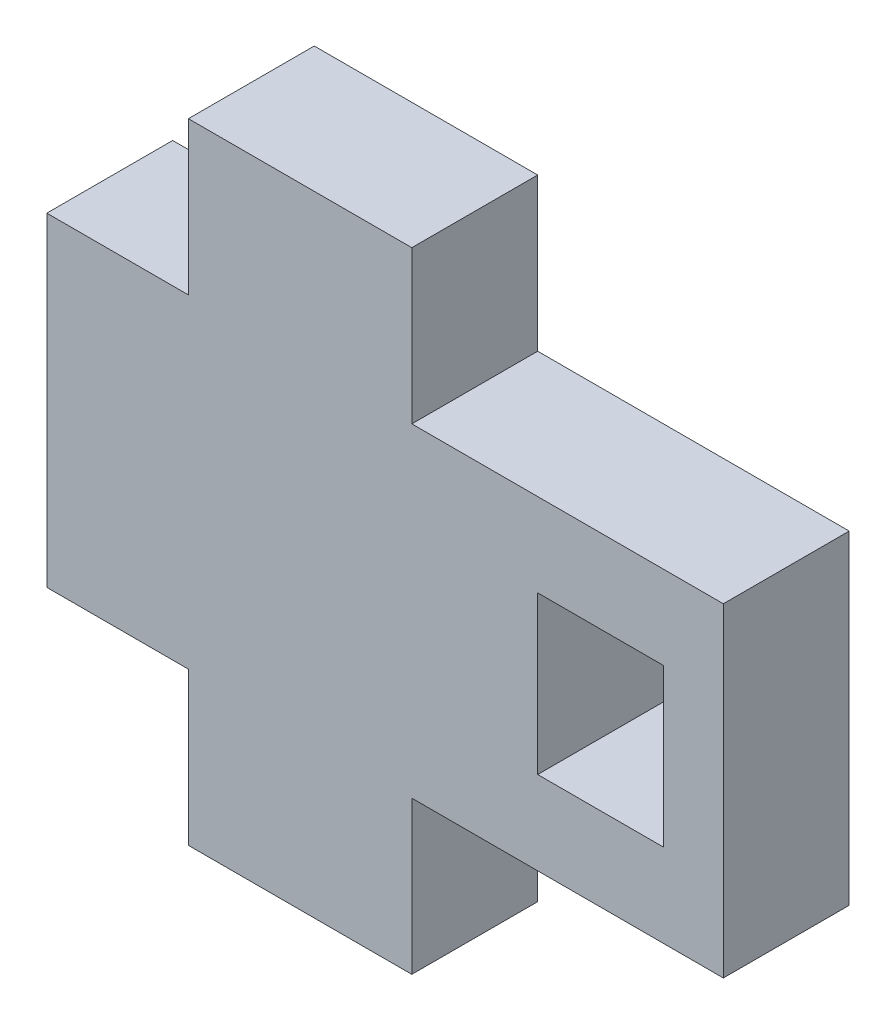
SolidWorks part; units mm, degrees
ref_plane "前视基准面" through (0, 0, 0) normal (0, 0, 1) x (1, 0, 0)
ref_plane "上视基准面" through (0, 0, 0) normal (0, 1, 0) x (1, 0, 0)
ref_plane "右视基准面" through (0, 0, 0) normal (1, 0, 0) x (0, 0, -1)
sketch "草图1" plane through (0, 0, 0) normal (0, 0, 1) x (1, 0, 0)
  line L0 (0, 15.15) -> (0, 20)
  line L1 (0, 0) -> (7.1, 0)
  line L2 (0, 0) -> (0, 4.85)
  line L3 (0, 20) -> (7.1, 20)
  line L4 (7.1, 0) -> (7.1, 4.85)
  line L5 (7.1, 15.15) -> (12.1, 15.15)
  line L7 (7.1, 4.85) -> (12.1, 4.85)
  line L9 (0, 15.15) -> (-4.5, 15.15)
  line L11 (0, 4.85) -> (-4.5, 4.85)
  line L12 (-4.5, 15.15) -> (-4.5, 4.85)
  line L13 (7.1, 15.15) -> (7.1, 20)
  line L15 (12.1, 15.15) -> (17, 15.15)
  line L17 (12.1, 4.85) -> (17, 4.85)
  line L18 (17, 15.15) -> (17, 4.85)
  line L19 (15.1, 12.5) -> (11.1, 12.5)
  line L20 (15.1, 12.5) -> (15.1, 7.5)
  line L21 (15.1, 7.5) -> (11.1, 7.5)
  line L22 (11.1, 12.5) -> (11.1, 7.5)
  point P19 (0, 0)
  point P20 (0, 0)
  point P21 (0, 0)
  point P22 (0, 0)
extrude "凸台-拉伸1" add sketch "草图1" along normal mid plane 4
